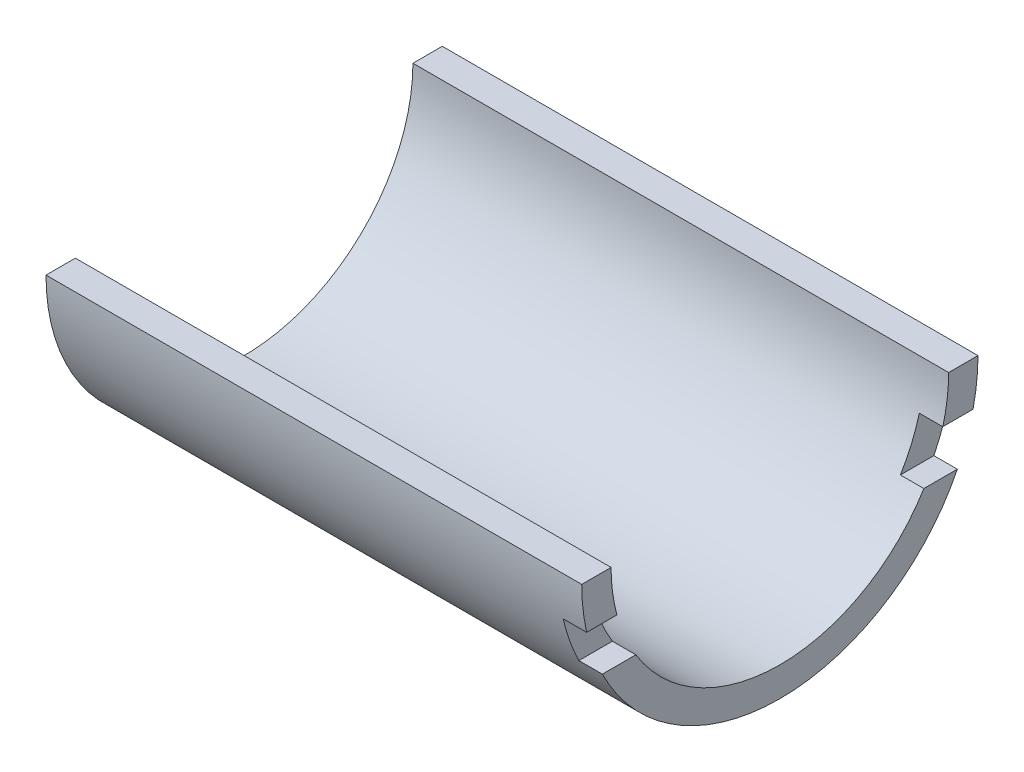
SolidWorks part; units mm, degrees
ref_plane "Front Plane" through (0, 0, 0) normal (0, 0, 1) x (1, 0, 0)
ref_plane "Top Plane" through (0, 0, 0) normal (0, 1, 0) x (1, 0, 0)
ref_plane "Right Plane" through (0, 0, 0) normal (1, 0, 0) x (0, 0, -1)
sketch "Sketch1" plane through (0, 0, 0) normal (1, 0, 0) x (0, 0, -1)
  line L0 (-27, 0) -> (-23, 0)
  line L1 (23, 0) -> (27, 0)
  arc A0 (-27, 0) -> (27, 0) centre (0, 0) ccw
  arc A1 (-23, 0) -> (23, 0) centre (0, 0) ccw
  point P6 (0, 0)
  dimension "D1" = 23
  dimension "D2" = 4
extrude "Boss-Extrude1" add sketch "Sketch1" along normal mid plane 73 contours L1 A0 L0 A1
sketch "Sketch2" plane through (0, 0, 0) normal (1, 0, 0) x (0, 0, -1)
  line L0 (-29.2115, -6) -> (28.0386, -6)
  line L1 (28.0386, -6) -> (28.0386, -12)
  line L2 (28.0386, -12) -> (-29.2115, -12)
  line L3 (-29.2115, -12) -> (-29.2115, -6)
  line L4 (-27, 0) -> (-23, 0) construction
  dimension "D1" = 6
  dimension "D2" = 6
extrude "Cut-Extrude1" cut sketch "Sketch2" against normal blind 3.2 and the other way through all from surface at 36.5 starting at face at (36.5, -12.5, 0)
